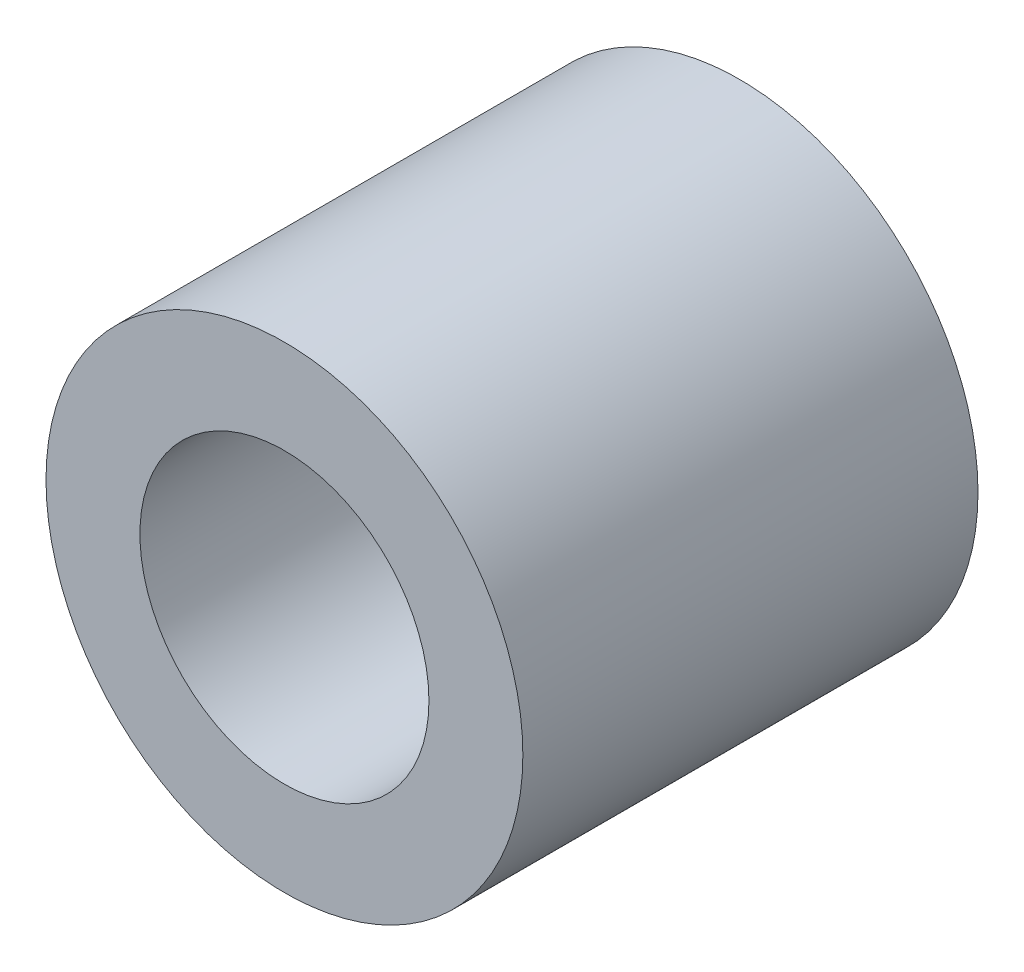
SolidWorks part; units mm, degrees
material "6061-T6 (SS)"
ref_plane "Piano frontale" through (0, 0, 0) normal (0, 0, 1) x (1, 0, 0)
ref_plane "Piano superiore" through (0, 0, 0) normal (0, 1, 0) x (1, 0, 0)
ref_plane "Piano destro" through (0, 0, 0) normal (1, 0, 0) x (0, 0, -1)
sketch "Schizzo1" plane through (0, 0, 0) normal (0, 0, 1) x (1, 0, 0)
  circle A0 centre (0, 0) radius 6.35
  circle A1 centre (0, 0) radius 10.4775
  dimension "D1" = 12.7
  dimension "D2" = 20.955
extrude "Estrusione-Estrusione1" add sketch "Schizzo1" along normal blind 20
cosmetic thread "Filettatura cosmetica1" parameters "D1"=15, "D2"=18.632
